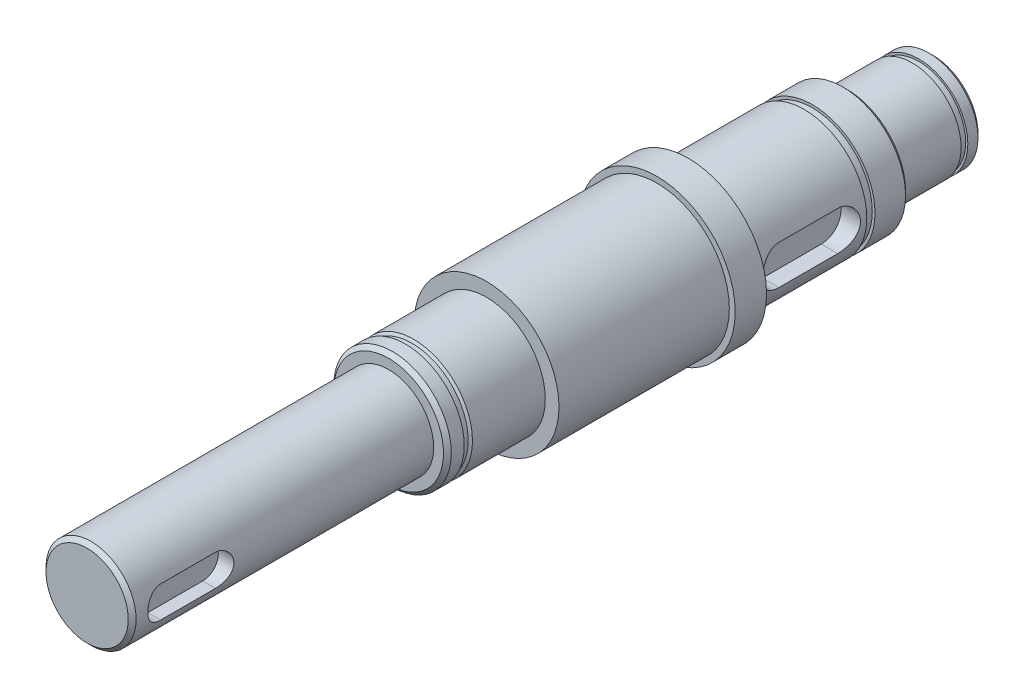
SolidWorks part; units mm, degrees
ref_plane "Piano frontale" through (0, 0, 0) normal (0, 0, 1) x (1, 0, 0)
ref_plane "Piano superiore" through (0, 0, 0) normal (0, 1, 0) x (1, 0, 0)
ref_plane "Piano destro" through (0, 0, 0) normal (1, 0, 0) x (0, 0, -1)
sketch "Schizzo4" plane through (0, 0, 0) normal (1, 0, 0) x (0, 0, -1)
  line L0 (0, 0) -> (216, 0)
  line L1 (216, 0) -> (216, 12.5)
  line L2 (216, 12.5) -> (194, 12.5)
  line L3 (194, 12.5) -> (194, 16)
  line L4 (194, 16) -> (153.5, 16)
  line L5 (153.5, 16) -> (153.5, 20)
  line L8 (102, 15) -> (77, 15)
  line L9 (77, 15) -> (77, 11.5)
  line L10 (77, 11.5) -> (0, 11.5)
  line L11 (0, 11.5) -> (0, 0)
  line L21 (145.5, 20) -> (153.5, 20)
  line L22 (102, 15) -> (102, 18.5)
  line L23 (102, 18.5) -> (145.5, 18.5)
  line L24 (145.5, 18.5) -> (145.5, 20)
  point P15 (102, 16.75)
  dimension "D1" = 11.5
  dimension "D2" = 12.5
  dimension "D3" = 8
  dimension "15" = 16
  dimension "D4" = 15
  dimension "D5" = 20
  dimension "D6" = 22
  dimension "D7" = 40.5
  dimension "D8" = 18.5
  dimension "D9" = 25
  dimension "D10" = 51.5
  dimension "210" = 216
revolve "Rivoluzione1" add sketch "Schizzo4" angle 360 about L0
sketch "Schizzo6" plane through (0, 0, 0) normal (1, 0, 0) x (0, 0, -1)
  line L0 (161.5, 0) -> (176.5, 0) construction
  line L1 (161.5, 5) -> (176.5, 5)
  line L2 (161.5, -5) -> (176.5, -5)
  line L4 (153.5, -16) -> (153.5, 16) construction
  arc A0 (161.5, 5) -> (161.5, -5) centre (161.5, 0) ccw
  arc A1 (176.5, -5) -> (176.5, 5) centre (176.5, 0) ccw
  point P3 (169, 0)
  dimension "D1" = 15
  dimension "D2" = 10
  dimension "D3" = 8
sketch "Schizzo8" plane through (0, 0, 0) normal (1, 0, 0) x (0, 0, -1)
  line L0 (8, 0) -> (22, 0) construction
  line L1 (8, 4) -> (22, 4)
  line L2 (8, -4) -> (22, -4)
  arc A0 (8, 4) -> (8, -4) centre (8, 0) ccw
  arc A1 (22, -4) -> (22, 4) centre (22, 0) ccw
  point P3 (15, 0)
  dimension "D1" = 8
  dimension "D2" = 14
  dimension "D3" = 8
sketch "Schizzo10" plane through (0, 0, 0) normal (1, 0, 0) x (0, 0, -1)
  line L0 (183.0959, 16) -> (183.5, 15.3)
  line L1 (194, 16) -> (153.5, 16) construction
  line L2 (183.5, 15.3) -> (185.2, 15.3)
  line L3 (185.2, 15.3) -> (185.2, 16)
  line L4 (185.2, 16) -> (183.0959, 16)
  line L5 (153.5, -16) -> (153.5, 16) construction
  line L6 (141.3907, 0) -> (225.7315, 0) construction
  dimension "D1" = 0.7
  dimension "D2" = 1.7
  dimension "D3" = 120
  dimension "D4" = 30
revolve "Taglia-Rivoluzione1" cut sketch "Schizzo10" angle 360 about L6
sketch "Schizzo11" plane through (0, 0, 0) normal (1, 0, 0) x (0, 0, -1)
  line L0 (210.6825, 12.5) -> (211, 11.95)
  line L1 (216, 12.5) -> (194, 12.5) construction
  line L2 (211, 11.95) -> (212.4, 11.95)
  line L3 (212.4, 11.95) -> (212.4, 12.5)
  line L4 (212.4, 12.5) -> (210.6825, 12.5)
  line L6 (194, -16) -> (194, 16) construction
  line L7 (146.2052, 0) -> (225.2564, 0) construction
  dimension "D1" = 0.55
  dimension "D2" = 1.4
  dimension "D3" = 120
  dimension "D4" = 17
revolve "Taglia-Rivoluzione2" cut sketch "Schizzo11" angle 360 about L7
sketch "Schizzo12" plane through (0, 0, 0) normal (1, 0, 0) x (0, 0, -1)
  line L0 (83.4041, 15) -> (83, 14.3)
  line L1 (102, 15) -> (77, 15) construction
  line L2 (83, 14.3) -> (81.3, 14.3)
  line L3 (81.3, 14.3) -> (81.3, 15)
  line L4 (81.3, 15) -> (83.4041, 15)
  line L6 (46.8842, 0) -> (71.5811, 0) construction
  line L7 (102, 15) -> (102, -15) construction
  dimension "D1" = 19
  dimension "D2" = 0.7
  dimension "D3" = 1.7
  dimension "D4" = 120
revolve "Taglia-Rivoluzione3" cut sketch "Schizzo12" angle 360 about L6
extrude "Taglio-Estrusione4" cut sketch "Schizzo6" against normal blind 5 from offset 16
extrude "Taglio-Estrusione5" cut sketch "Schizzo8" against normal blind 4 from offset 11.5
chamfer "Smusso5" distance 1 angle 45 4 edges at (12.5, 0, -216) (16, 0, -194) (15, 0, -77) (11.5, 0, 0)
